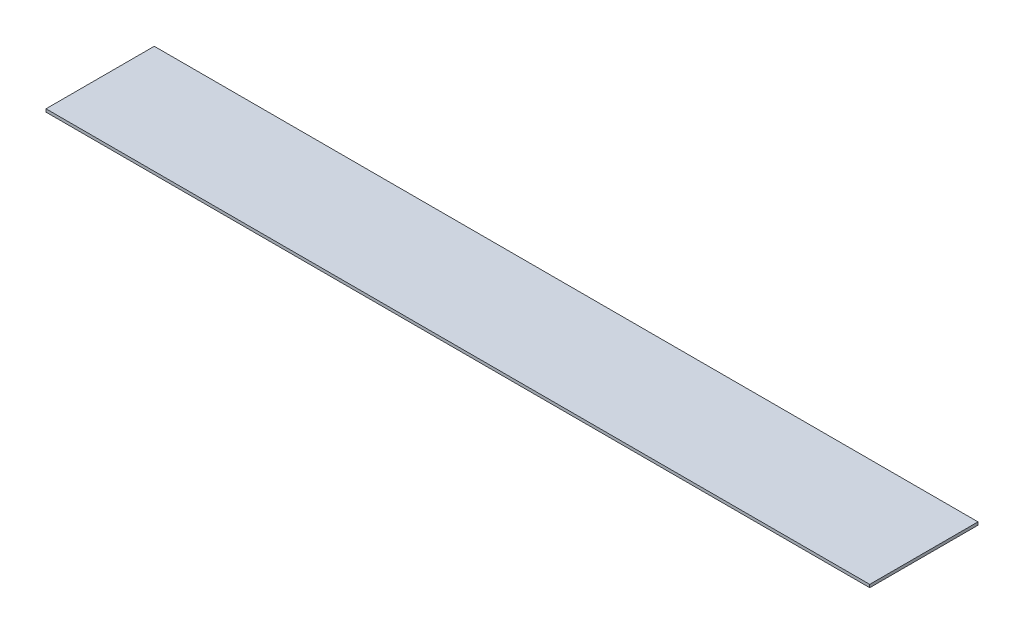
SolidWorks part; units mm, degrees
ref_plane "Front Plane" through (0, 0, 0) normal (0, 0, 1) x (1, 0, 0)
ref_plane "Top Plane" through (0, 0, 0) normal (0, 1, 0) x (1, 0, 0)
ref_plane "Right Plane" through (0, 0, 0) normal (1, 0, 0) x (0, 0, -1)
sketch "Sketch1" plane through (0, 0, 0) normal (0, 1, 0) x (1, 0, 0)
  line L1 (-893.7625, -117.475) -> (893.7625, -117.475)
  line L2 (-893.7625, -117.475) -> (-893.7625, 117.475)
  line L3 (-893.7625, 117.475) -> (893.7625, 117.475)
  line L4 (893.7625, -117.475) -> (893.7625, 117.475)
  line L5 (-893.7625, -117.475) -> (893.7625, 117.475) construction
  line L6 (-893.7625, 117.475) -> (893.7625, -117.475) construction
  point P0 (0, 0)
  dimension "D1" = 1787.525
  dimension "D2" = 234.95
extrude "Boss-Extrude1" add sketch "Sketch1" along normal blind 6.35
